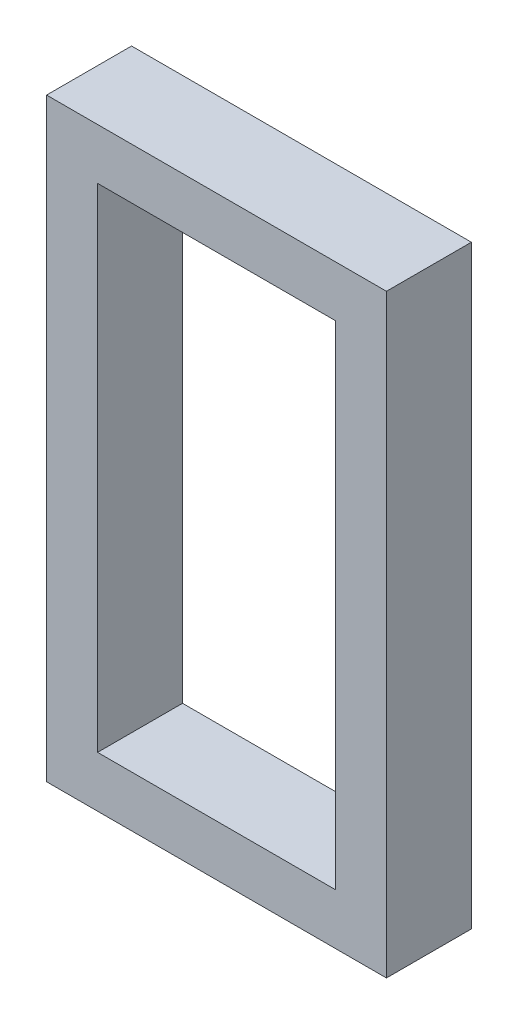
SolidWorks part; units mm, degrees
ref_plane "Front Plane" through (0, 0, 0) normal (0, 0, 1) x (1, 0, 0)
ref_plane "Top Plane" through (0, 0, 0) normal (0, 1, 0) x (1, 0, 0)
ref_plane "Right Plane" through (0, 0, 0) normal (1, 0, 0) x (0, 0, -1)
sketch "Sketch1" plane through (0, 0, 0) normal (0, 0, 1) x (1, 0, 0)
  line L0 (-12.7, 0) -> (12.7, 0)
  line L1 (12.7, 0) -> (12.7, 44.45)
  line L2 (12.7, 44.45) -> (-12.7, 44.45)
  line L3 (-12.7, 44.45) -> (-12.7, 0)
  dimension "D1" = 25.4
  dimension "D2" = 44.45
  dimension "D3" = 25.4
  dimension "D4" = 12.7
extrude "Boss-Extrude1" add sketch "Sketch1" along normal blind 6.35
sketch "Sketch3" plane through (0, 0, 6.35) normal (0, 0, 1) x (1, 0, 0)
  line L8 (-8.89, 40.64) -> (-8.89, 3.81)
  line L9 (-8.89, 3.81) -> (8.89, 3.81)
  line L10 (8.89, 3.81) -> (8.89, 40.64)
  line L11 (8.89, 40.64) -> (-8.89, 40.64)
  line L12 (-8.89, 40.64) -> (-8.89, 3.81)
  line L13 (-8.89, 3.81) -> (8.89, 3.81)
  line L14 (8.89, 3.81) -> (8.89, 40.64)
  line L15 (8.89, 40.64) -> (-8.89, 40.64)
  dimension "D1" = 3.81
extrude "Cut-Extrude1" cut sketch "Sketch3" against normal blind 6.35 contours L12 L13 L14 L15
